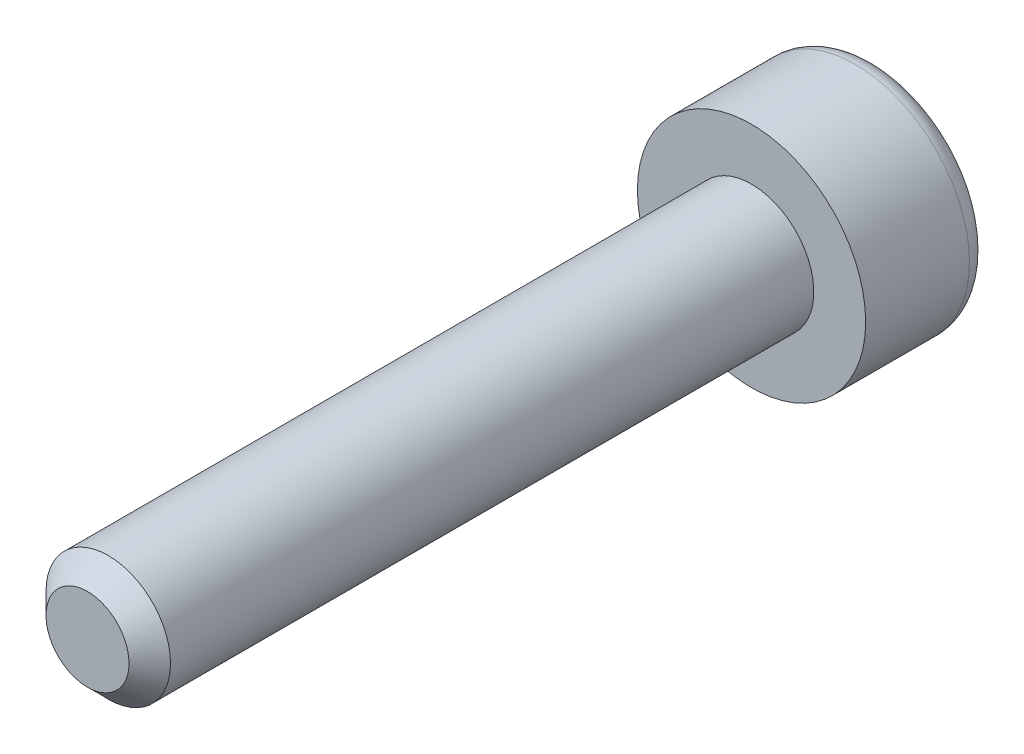
SolidWorks part; units mm, degrees
ref_plane "Face" through (0, 0, 0) normal (0, 0, 1) x (1, 0, 0)
ref_plane "Dessus" through (0, 0, 0) normal (0, 1, 0) x (1, 0, 0)
ref_plane "Droite" through (0, 0, 0) normal (1, 0, 0) x (0, 0, -1)
sketch "Esquisse1" plane through (0, 0, 0) normal (0, 0, 1) x (1, 0, 0)
  circle A0 centre (0, 0) radius 1.5
  dimension "D1" = 3
extrude "Base-Extrusion" add sketch "Esquisse1" along normal blind 16
chamfer "Chanfrein1" distance 0.5 angle 45 1 edges at (1.5, 0, 16)
sketch "Esquisse2" plane through (0, 0, 0) normal (0, 0, -1) x (-1, 0, 0)
  circle A0 centre (0, 0) radius 2.75
  dimension "D1" = 5.5
extrude "Boss.-Extru.1" add sketch "Esquisse2" along normal blind 3
fillet "Congé1" radius 0.5 1 edges at (-2.75, 0, -3)
sketch "Esquisse3" plane through (0, 0, -3) normal (0, 0, -1) x (-1, 0, 0)
  line L1 (0, 1.7321) -> (-1.5, 0.866)
  line L2 (-1.5, 0.866) -> (-1.5, -0.866)
  line L3 (-1.5, -0.866) -> (0, -1.7321)
  line L4 (0, -1.7321) -> (1.5, -0.866)
  line L5 (1.5, -0.866) -> (1.5, 0.866)
  line L6 (1.5, 0.866) -> (0, 1.7321)
  circle A0 centre (0, 0) radius 1.5 construction
  dimension "D1" = 3
extrude "Enlèv. mat.-Extru.1" cut sketch "Esquisse3" against normal blind 2
